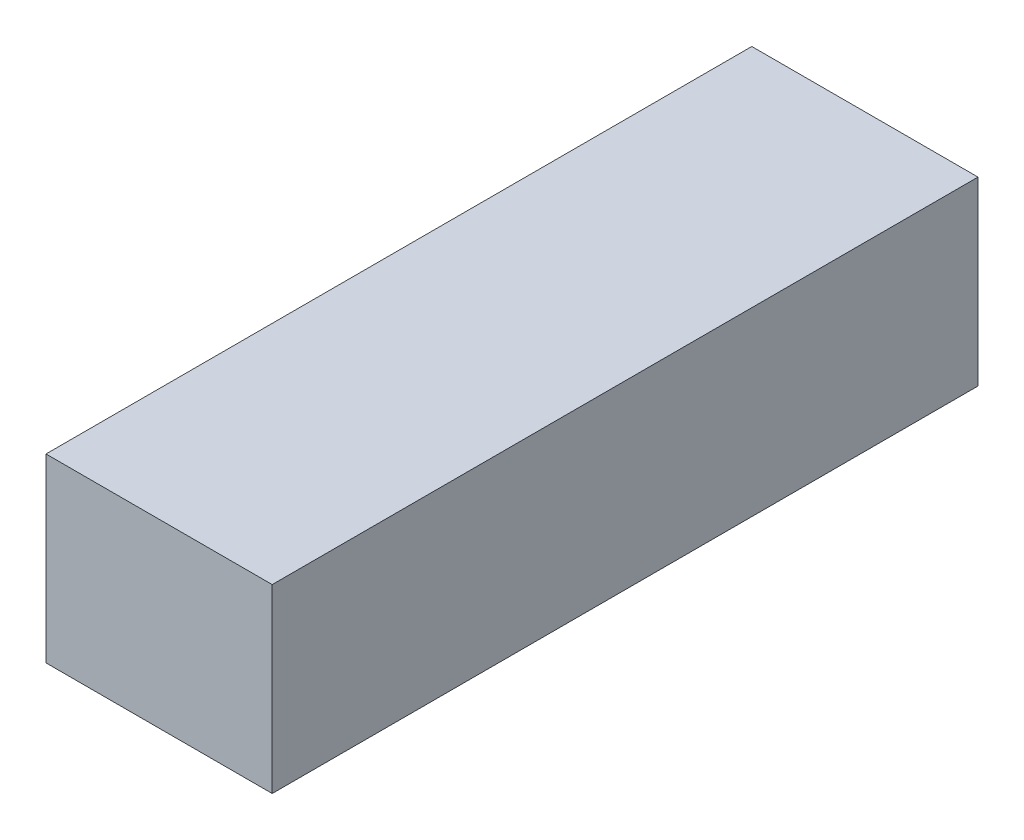
SolidWorks part; units mm, degrees
ref_plane "Front Plane" through (0, 0, 0) normal (0, 0, 1) x (1, 0, 0)
ref_plane "Top Plane" through (0, 0, 0) normal (0, 1, 0) x (1, 0, 0)
ref_plane "Right Plane" through (0, 0, 0) normal (1, 0, 0) x (0, 0, -1)
sketch "Sketch1" plane through (0, 0, 0) normal (0, 0, 1) x (1, 0, 0)
  line L1 (0, 0) -> (25, 0)
  line L2 (0, 0) -> (0, -20)
  line L3 (0, -20) -> (25, -20)
  line L4 (25, 0) -> (25, -20)
  dimension "D1" = 25
  dimension "D2" = 20
extrude "Boss-Extrude2" add sketch "Sketch1" along normal blind 78
